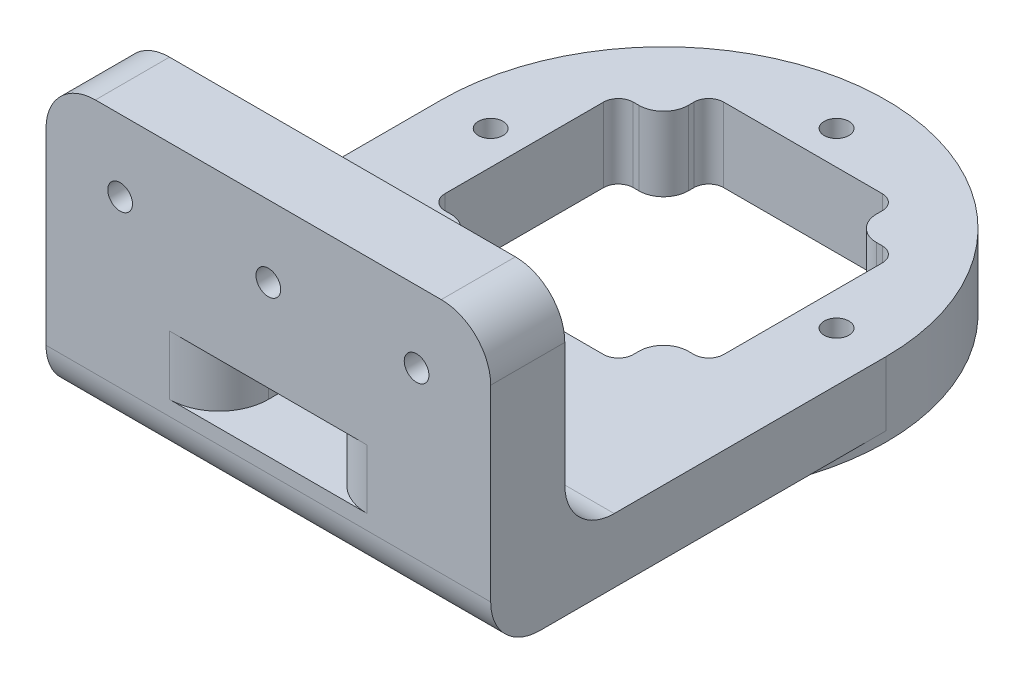
SolidWorks part; units mm, degrees
ref_plane "Front Plane" through (0, 0, 0) normal (0, 0, 1) x (1, 0, 0)
ref_plane "Top Plane" through (0, 0, 0) normal (0, 1, 0) x (1, 0, 0)
ref_plane "Right Plane" through (0, 0, 0) normal (1, 0, 0) x (0, 0, -1)
sketch "Sketch1" plane through (0, 0, 0) normal (0, 1, 0) x (1, 0, 0)
  line L0 (-16.05, 28.2) -> (16.05, 28.2)
  line L1 (-28.2, 16.05) -> (-28.2, -16.05)
  line L2 (-16.05, -28.2) -> (16.05, -28.2)
  line L3 (28.2, 16.05) -> (28.2, -16.05)
  line L4 (-25.2, 19.05) -> (-24.05, 19.05)
  line L5 (-19.05, 25.2) -> (-19.05, 24.05)
  line L6 (25.2, 19.05) -> (24.05, 19.05)
  line L7 (19.05, 25.2) -> (19.05, 24.05)
  line L8 (-24.05, -19.05) -> (-25.2, -19.05)
  line L9 (-19.05, -24.05) -> (-19.05, -25.2)
  line L10 (24.05, -19.05) -> (25.2, -19.05)
  line L11 (19.05, -24.05) -> (19.05, -25.2)
  line L12 (-45, -80) -> (45, -80)
  line L14 (-45, -80) -> (-45, 0)
  line L15 (-45, 0) -> (45, 0)
  line L16 (45, -80) -> (45, 0)
  line L17 (0, -45) -> (45, 0) construction
  line L18 (-45, 0) -> (0, -45) construction
  circle A0 centre (0, 0) radius 45
  arc A1 (24.05, 19.05) -> (19.05, 24.05) centre (24.05, 24.05) cw
  arc A2 (-24.05, 19.05) -> (-19.05, 24.05) centre (-24.05, 24.05) ccw
  arc A3 (-24.05, -19.05) -> (-19.05, -24.05) centre (-24.05, -24.05) cw
  arc A4 (19.05, -24.05) -> (24.05, -19.05) centre (24.05, -24.05) cw
  arc A5 (-28.2, 16.05) -> (-25.2, 19.05) centre (-25.2, 16.05) cw
  arc A6 (-28.2, -16.05) -> (-25.2, -19.05) centre (-25.2, -16.05) ccw
  arc A7 (-16.05, -28.2) -> (-19.05, -25.2) centre (-16.05, -25.2) cw
  arc A8 (16.05, -28.2) -> (19.05, -25.2) centre (16.05, -25.2) ccw
  arc A9 (25.2, -19.05) -> (28.2, -16.05) centre (25.2, -16.05) ccw
  arc A10 (28.2, 16.05) -> (25.2, 19.05) centre (25.2, 16.05) ccw
  arc A11 (16.05, 28.2) -> (19.05, 25.2) centre (16.05, 25.2) cw
  arc A12 (-19.05, 25.2) -> (-16.05, 28.2) centre (-16.05, 25.2) cw
  point P0 (0, 0)
  point P5 (0, 0)
  point P40 (0, -45)
  dimension "D2" = 90
  dimension "D3" = 5
  dimension "D4" = 3
  dimension "D1" = 28.2
  dimension "D5" = 32.1
  dimension "D6" = 32.1
  dimension "D7" = 80
extrude "Boss-Extrude1" add sketch "Sketch1" along normal blind 15 contours A0 L14 L12 L16 | A9 L10 A4 L11 A8 L2 A7 L9 A3 L8 A6 L1 L15 A0 L3 | L5 A12 L0 A11 L7 A1 L6 A10 L3 L15 A0 L1 A5 L4 A2
sketch "Sketch2" plane through (0, 15, 0) normal (0, 1, 0) x (1, 0, 0)
  line L0 (45, -80) -> (45, 0) construction
  line L1 (-45, -80) -> (45, -80)
  line L2 (-45, -80) -> (-45, -65)
  line L3 (-45, -65) -> (45, -65)
  line L4 (45, -80) -> (45, -65)
  circle A0 centre (0, 0) radius 40
  line M27 (45, -80) -> (45, 0)
  line M29 (-45, 0) -> (-45, -80)
  line M30 (-45, -80) -> (45, -80)
  dimension "D1" = 80
  dimension "D3" = 15
extrude "Boss-Extrude2" add sketch "Sketch2" along normal blind 45 contours L3 M29 M30 M27
sketch "Sketch3" plane through (0, 0, 0) normal (0, -1, 0) x (-1, 0, 0)
  line L1 (45, -80) -> (-45, -80)
  line L2 (45, -80) -> (45, 0)
  line L4 (-45, -80) -> (-45, 0)
  arc A0 (-45, 0) -> (45, 0) centre (0, 0) ccw
extrude "Cut-Extrude1" cut sketch "Sketch3" against normal blind 2
sketch "Sketch4" plane through (0, 0, 0) normal (0, -1, 0) x (-1, 0, 0)
  circle A0 centre (0, 0) radius 35
  circle A1 centre (0, -35) radius 2.5
  circle A2 centre (-35, 0) radius 2.5
  circle A3 centre (0, 35) radius 2.5
  circle A4 centre (35, 0) radius 2.5
  point P14 (0, 0)
  dimension "D1" = 70
  dimension "D2" = 5
  dimension "D3" = 4
extrude "Cut-Extrude2" cut sketch "Sketch4" against normal through all contours A1 | A2 | A4 | A3
fillet "Fillet1" radius 10 4 edges at (-45, 60, 72.5) (45, 60, 72.5) (0, 15, 65) (0, 2, 80)
sketch "Sketch5" plane through (0, 0, 65) normal (0, 0, -1) x (-1, 0, 0)
  circle A0 centre (-30, 45.5029) radius 2.5
  circle A1 centre (30, 45.5029) radius 2.5
  circle A2 centre (0, 45.5029) radius 2.5
  point P6 (0, 0)
  dimension "D1" = 5
  dimension "D2" = 5
  dimension "D3" = 5
  dimension "D4" = 30
  dimension "D5" = 30
  dimension "D6" = 45.5029
extrude "Cut-Extrude3" cut sketch "Sketch5" against normal through all
sketch "Sketch6" plane through (0, 15, 0) normal (0, 1, 0) x (1, 0, 0)
  line L0 (15, -50) -> (-15, -50)
  line L1 (-15, -50) -> (15, -50) construction
  line L2 (-15, -47.5) -> (15, -47.5)
  line L3 (-15, -52.5) -> (15, -52.5)
  line L4 (-45, -55) -> (45, -55) construction
  arc A0 (-15, -47.5) -> (-15, -52.5) centre (-15, -50) ccw
  arc A1 (15, -52.5) -> (15, -47.5) centre (15, -50) ccw
  point P0 (0, -50)
  point P3 (0, -50)
  dimension "D2" = 2.5
  dimension "D1" = 30
  dimension "D3" = 5
extrude "Cut-Extrude4" cut sketch "Sketch6" against normal through all
sketch "Sketch7" plane through (0, 2, 0) normal (0, -1, 0) x (1, 0, 0)
  line L0 (-15, 50) -> (15, 50) construction
  line L1 (-15, 54) -> (15, 54)
  line L2 (-15, 46) -> (15, 46)
  arc A0 (-15, 54) -> (-15, 46) centre (-15, 50) ccw
  arc A1 (15, 46) -> (15, 54) centre (15, 50) ccw
  point P4 (0, 50)
  dimension "D1" = 4
extrude "Cut-Extrude5" cut sketch "Sketch7" against normal blind 4
sketch "Sketch8" plane through (0, 0, 65) normal (0, 0, -1) x (-1, 0, 0)
  line L1 (-10, 27) -> (10, 27)
  line L2 (-10, 27) -> (-10, 15)
  line L3 (-10, 15) -> (10, 15)
  line L4 (10, 27) -> (10, 15)
  line L6 (45, 15) -> (-45, 15) construction
  point P8 (0, 27)
  dimension "D1" = 20
  dimension "D2" = 12
extrude "Cut-Extrude6" cut sketch "Sketch8" against normal up to vertex (15 mm away) and the other way blind 10
fillet "Fillet2" radius 10 2 edges at (-10, 21, 80) (10, 21, 80)
